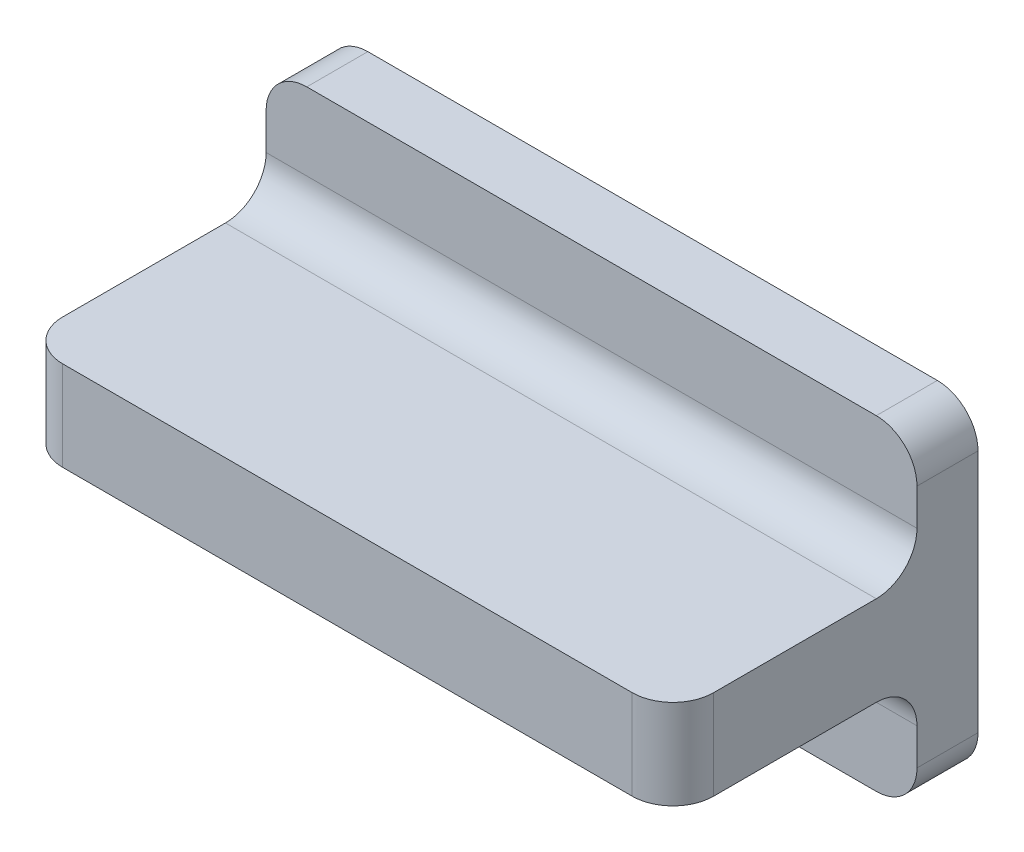
SolidWorks part; units mm, degrees
material "ABS"
ref_plane "X-Y Datum" through (0, 0, 0) normal (0, 0, 1) x (1, 0, 0)
ref_plane "X-Z Datum" through (0, 0, 0) normal (0, 1, 0) x (1, 0, 0)
ref_plane "Y-Z Datum" through (0, 0, 0) normal (1, 0, 0) x (0, 0, -1)
sketch "Sketch1" plane through (0, 0, 0) normal (0, 0, 1) x (1, 0, 0)
  line L1 (-25.4, 12.7) -> (25.4, 12.7)
  line L2 (-25.4, 12.7) -> (-25.4, -12.7)
  line L3 (-25.4, -12.7) -> (25.4, -12.7)
  line L4 (25.4, 12.7) -> (25.4, -12.7)
  line L5 (-25.4, 12.7) -> (25.4, -12.7) construction
  line L6 (-25.4, -12.7) -> (25.4, 12.7) construction
  point P0 (0, 0)
  dimension "D1" = 50.8
  dimension "D2" = 25.4
extrude "Boss-Extrude1" add sketch "Sketch1" along normal blind 4.7625
sketch "Sketch2" plane through (0, 0, 4.7625) normal (0, 0, 1) x (1, 0, 0)
  line L0 (25.4, -12.7) -> (25.4, 12.7) construction
  line L1 (-25.4, 3.5) -> (25.4, 3.5)
  line L2 (-25.4, 3.5) -> (-25.4, -3.5)
  line L3 (-25.4, -3.5) -> (25.4, -3.5)
  line L4 (25.4, 3.5) -> (25.4, -3.5)
  line L5 (-25.4, 3.5) -> (25.4, -3.5) construction
  line L6 (-25.4, -3.5) -> (25.4, 3.5) construction
  point P0 (0, 0)
  dimension "D1" = 7
extrude "Boss-Extrude2" add sketch "Sketch2" along normal blind 19.05
fillet "Fillet1" radius 3.175 8 edges at (0, 3.5, 4.7625) (0, -3.5, 4.7625) (-25.4, 0, 23.8125) (25.4, 0, 23.8125) (25.4, 12.7, 2.3813) (25.4, -12.7, 2.3813) (-25.4, 12.7, 2.3813) (-25.4, -12.7, 2.3813)
